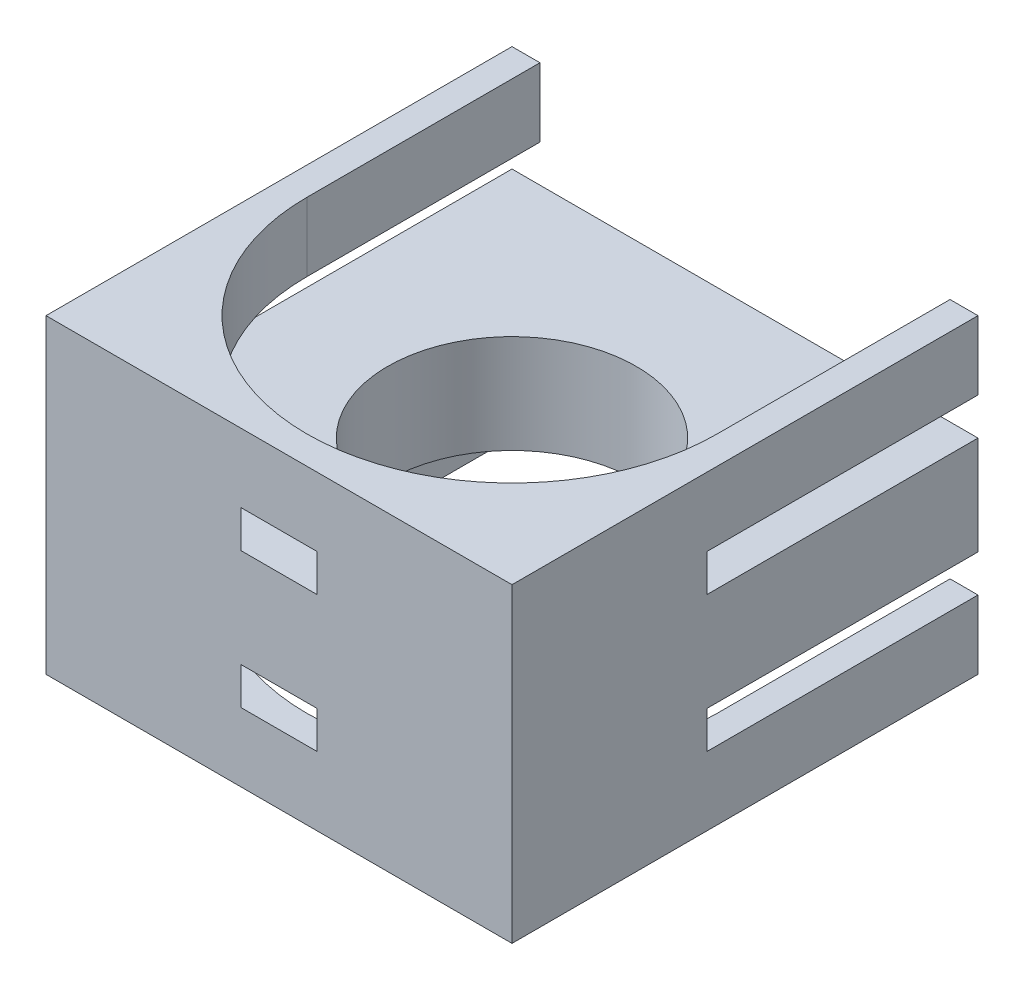
SolidWorks part; units mm, degrees
ref_plane "Front Plane" through (0, 0, 0) normal (0, 0, 1) x (1, 0, 0)
ref_plane "Top Plane" through (0, 0, 0) normal (0, 1, 0) x (1, 0, 0)
ref_plane "Right Plane" through (0, 0, 0) normal (1, 0, 0) x (0, 0, -1)
sketch "Sketch1" plane through (0, 0, 0) normal (0, 1, 0) x (1, 0, 0)
  line L8 (15, 0) -> (0, 0)
  line L11 (15, -15) -> (15, 0)
  line L15 (15, -15) -> (0, -15)
  line L16 (0, -15) -> (0, 0)
  point P0 (0, 0)
  dimension "D1" = 15
  dimension "D2" = 15
extrude "Boss-Extrude1" add sketch "Sketch1" along normal blind 5
sketch "Sketch2" plane through (0, 0, 15) normal (0, 0, 1) x (1, 0, 0)
  line L0 (0, 5) -> (0, 7.5)
  line L1 (0, 7.5) -> (15, 7.5)
  line L2 (15, 7.5) -> (15, 5)
  line L3 (15, 5) -> (0, 5)
  line L4 (0, 0) -> (15, 0)
  line L5 (15, 0) -> (15, -2.5)
  line L6 (15, -2.5) -> (0, -2.5)
  line L7 (0, -2.5) -> (0, 0)
  dimension "D1" = 10
extrude "Boss-Extrude2" add sketch "Sketch2" against normal up to surface (15 mm away) up to face at (7.5, 2.5, 0)
ref_plane "Plane1" through (0, 2.5, 0) normal (0, -1, 0) x (-1, 0, 0)
sketch "Sketch3" plane through (0, 0, 0) normal (0, 0, -1) x (-1, 0, 0)
  line L0 (-14.1, 7.5) -> (-14.1, 5.2875)
  line L1 (0, 7.5) -> (-15, 7.5) construction
  line L2 (-14.1, 5.2875) -> (-15.1, 5.2875)
  line L3 (-15.1, 5.2875) -> (-15.1, 4.0875)
  line L4 (-15.1, 4.0875) -> (-7.5, 4.0875)
  line L5 (-7.5, 4.0875) -> (0.1, 4.0875)
  line L6 (0.1, 4.0875) -> (0.1, 5.2875)
  line L7 (0.1, 5.2875) -> (-0.9, 5.2875)
  line L8 (-0.9, 5.2875) -> (-0.9, 7.5)
  line L9 (-0.9, 7.5) -> (-14.1, 7.5)
  line L10 (-15, 2.5) -> (0, 2.5) construction
  line L13 (-7.5, 2.5) -> (-7.5, 4.0875) construction
  line L14 (0, 7.5) -> (0, -2.5) construction
  line L15 (-15, 7.5) -> (-15, -2.5) construction
  point P13 (-18.0374, 1.1286)
  point P14 (0, 2.5)
  point P15 (0, 0)
  point P19 (-15, 2.5)
  dimension "D1" = 1.2
  dimension "D2" = 3.4125
  dimension "D3" = 13.2
  dimension "D4" = 15.2
extrude "Cut-Extrude1" cut sketch "Sketch3" against normal blind 7.5 and the other way through all
sketch "Sketch4" plane through (0, 4.0875, 0) normal (0, 1, 0) x (1, 0, 0)
  line L1 (0, 0) -> (0, -15) construction
  line L2 (0, -7.5) -> (15, -7.5) construction
  line L3 (15, 0) -> (15, -15) construction
  circle A0 centre (7.5, -7.5) radius 7.6
  point P2 (7.5, -7.5)
  dimension "D1" = 15.2
extrude "Cut-Extrude2" cut sketch "Sketch4" along normal up to surface (1.2 mm away) up to face at (0.45, 5.2875, 3.75)
sketch "Sketch5" plane through (0, 4.0875, 0) normal (0, 1, 0) x (1, 0, 0)
  circle A0 centre (7.5, -7.5) radius 6.6
  circle A1 centre (7.5, -7.5) radius 7.6 construction
  dimension "D1" = 13.2
extrude "Cut-Extrude3" cut sketch "Sketch5" along normal through all
mirror "Mirror1" about plane through (0, 2.5, 0) normal (0, -1, 0) of "Cut-Extrude1"
sketch "Sketch6" plane through (0, 0.9125, 0) normal (0, -1, 0) x (1, 0, 0)
  circle A0 centre (7.5, 7.5) radius 7.6
  circle A1 centre (7.5, 7.5) radius 7.6 construction
  dimension "D1" = 15.2
extrude "Cut-Extrude4" cut sketch "Sketch6" along normal up to surface (1.2 mm away) up to face at (0.45, -0.2875, 3.75)
sketch "Sketch7" plane through (0, 0.9125, 0) normal (0, -1, 0) x (1, 0, 0)
  circle A0 centre (7.5, 7.5) radius 6.6
  circle A1 centre (7.5, 7.5) radius 7.6 construction
  dimension "D1" = 13.2
extrude "Cut-Extrude5" cut sketch "Sketch7" along normal through all
sketch "Sketch8" plane through (0, 4.0875, 0) normal (0, 1, 0) x (1, 0, 0)
  circle A0 centre (7.5, -7.5) radius 4
  dimension "D1" = 8
extrude "Cut-Extrude6" cut sketch "Sketch8" against normal through all
